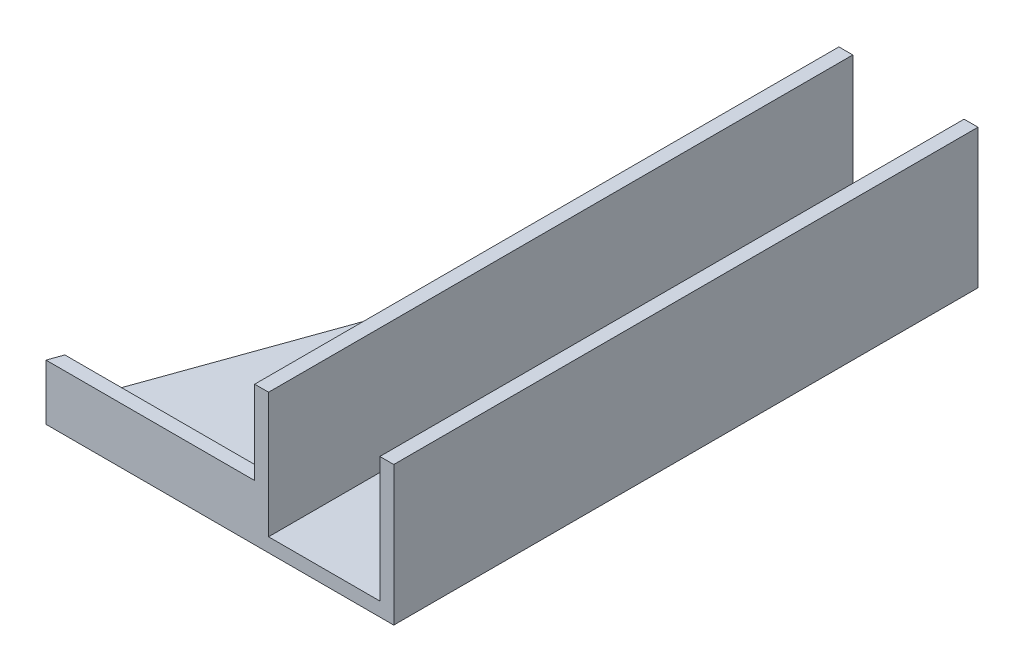
SolidWorks part; units mm, degrees
ref_plane "Front Plane" through (0, 0, 0) normal (0, 0, 1) x (1, 0, 0)
ref_plane "Top Plane" through (0, 0, 0) normal (0, 1, 0) x (1, 0, 0)
ref_plane "Right Plane" through (0, 0, 0) normal (1, 0, 0) x (0, 0, -1)
sketch "Sketch1" plane through (0, 0, 0) normal (0, 1, 0) x (1, 0, 0)
  line L0 (-37.5, -105) -> (37.5, 105)
  line L1 (-37.5, -105) -> (37.5, -105)
  line L4 (37.5, -105) -> (37.5, 105)
  line L5 (-37.5, -105) -> (37.5, 105) construction
  line L6 (0, 0) -> (37.5, -105) construction
  point P0 (0, 0)
  dimension "D1" = 210
extrude "Boss-Extrude1" add sketch "Sketch1" along normal blind 5
sketch "Sketch2" plane through (0, 5, 0) normal (0, 1, 0) x (1, 0, 0)
  line L0 (37.5, -105) -> (37.5, 105) construction
  line L1 (-37.5, -105) -> (37.5, -105)
  line L3 (-35.7143, -100) -> (37.5, -100)
  line L4 (37.5, -105) -> (37.5, -100)
  line L5 (-37.5, -105) -> (-35.7143, -100)
  line L6 (37.5, 105) -> (-37.5, -105) construction
  dimension "D1" = 5
extrude "Boss-Extrude2" add sketch "Sketch2" along normal blind 15
sketch "Sketch3" plane through (0, 0, 0) normal (0, -1, 0) x (1, 0, 0)
  line L0 (37.5, 105) -> (84.0815, 105) construction
  line L2 (37.5, -105) -> (87.5, -105)
  line L3 (37.5, -105) -> (37.5, 105)
  line L4 (37.5, 105) -> (87.5, 105)
  line L5 (87.5, -105) -> (87.5, 105)
  dimension "D1" = 50
extrude "Boss-Extrude3" add sketch "Sketch3" against normal blind 50
sketch "Sketch4" plane through (0, 0, -105) normal (0, 0, -1) x (-1, 0, 0)
  line L0 (-37.5, 0) -> (-87.5, 0) construction
  line L2 (-42.5, 5) -> (-42.5, 50)
  line L3 (-42.5, 50) -> (-82.5, 50)
  line L4 (-82.5, 5) -> (-82.5, 50)
  line L5 (-37.5, 50) -> (-87.5, 50) construction
  line L6 (-37.5, 50) -> (-37.5, 5) construction
  line L7 (-87.5, 50) -> (-87.5, 0) construction
  line L8 (-42.5, 5) -> (-82.5, 5)
  dimension "D1" = 5
  dimension "D2" = 5
  dimension "D3" = 5
extrude "Cut-Extrude2" cut sketch "Sketch4" against normal up to surface (210 mm away) up to face at (29.1667, 23.3333, 105)
